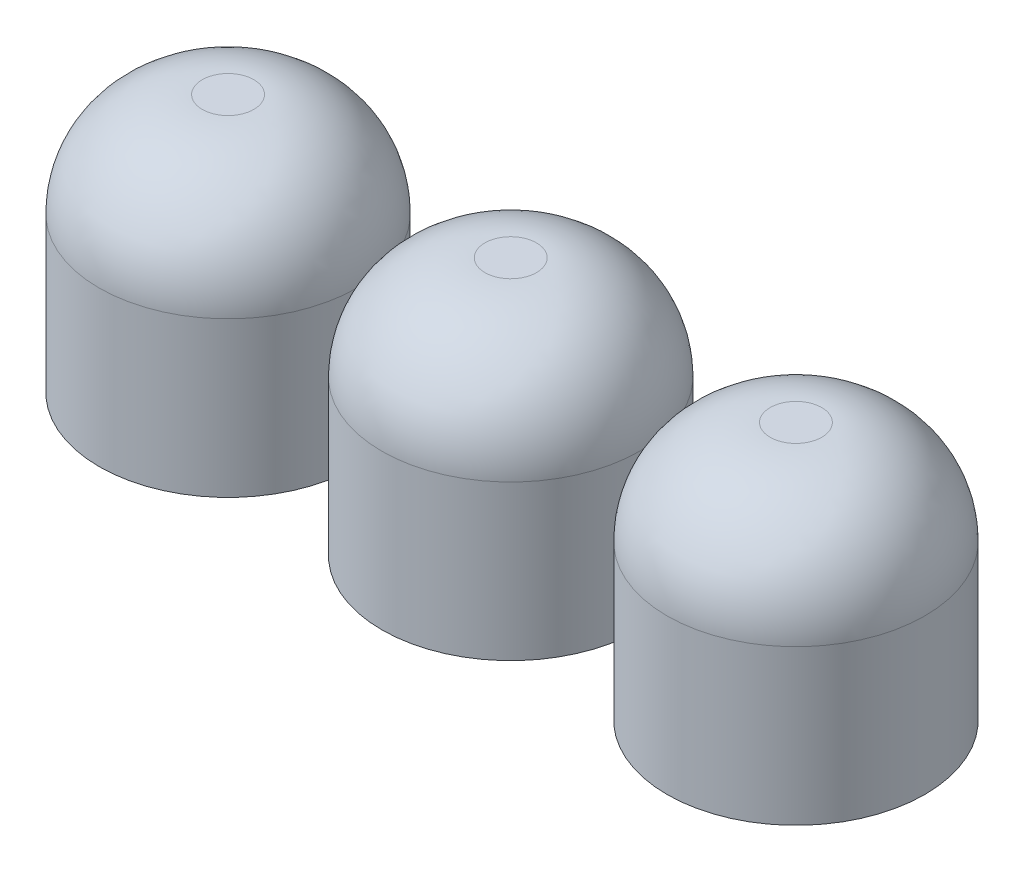
SolidWorks part; units mm, degrees
ref_plane "Front Plane" through (0, 0, 0) normal (0, 0, 1) x (1, 0, 0)
ref_plane "Top Plane" through (0, 0, 0) normal (0, 1, 0) x (1, 0, 0)
ref_plane "Right Plane" through (0, 0, 0) normal (1, 0, 0) x (0, 0, -1)
sketch "Sketch1" plane through (0, 0, 0) normal (0, 1, 0) x (1, 0, 0)
  circle A0 centre (-28.3181, 2.4368) radius 2.5
  circle A1 centre (-22.8359, 2.4368) radius 2.5
  circle A2 centre (-17.3041, 2.4368) radius 2.5
  circle A3 centre (-28.3181, 2.4368) radius 2
  circle A4 centre (-22.8359, 2.4368) radius 2
  circle A5 centre (-17.3041, 2.4368) radius 2
  point P9 (-22.5042, 2.4368)
  point P10 (-16.9212, 2.4368)
  point P11 (-22.8359, 2.4368)
  point P12 (-17.3041, 2.4368)
  dimension "D1" = 4
  dimension "D2" = 5
  dimension "D3" = 5
  dimension "D4" = 4
  dimension "D5" = 4
  dimension "D6" = 5
extrude "Boss-Extrude1" add sketch "Sketch1" along normal blind 5
sketch "Sketch2" plane through (0, 0, 0) normal (0, 1, 0) x (1, 0, 0)
  circle A2 centre (-22.8359, 2.4368) radius 2
  circle A3 centre (-17.3041, 2.4368) radius 2
  circle A5 centre (-28.3181, 2.4368) radius 2
extrude "Boss-Extrude2" add sketch "Sketch2" along normal blind 5
sketch "Sketch3" plane through (0, 0, 0) normal (0, -1, 0) x (-1, 0, 0)
  circle A0 centre (28.3181, 2.4368) radius 2.05
  circle A1 centre (22.8359, 2.4368) radius 2.05
  circle A2 centre (17.3041, 2.4368) radius 2.05
  dimension "D1" = 4.1
  dimension "D2" = 4.1
  dimension "D3" = 4.1
extrude "Cut-Extrude1" cut sketch "Sketch3" against normal blind 4
fillet "Fillet1" radius 2 1 edges at (-28.3181, 5, 0.0632)
fillet "Fillet2" radius 2 1 edges at (-22.8359, 5, 0.0632)
fillet "Fillet4" radius 2 1 edges at (-17.3041, 5, 0.0632)
